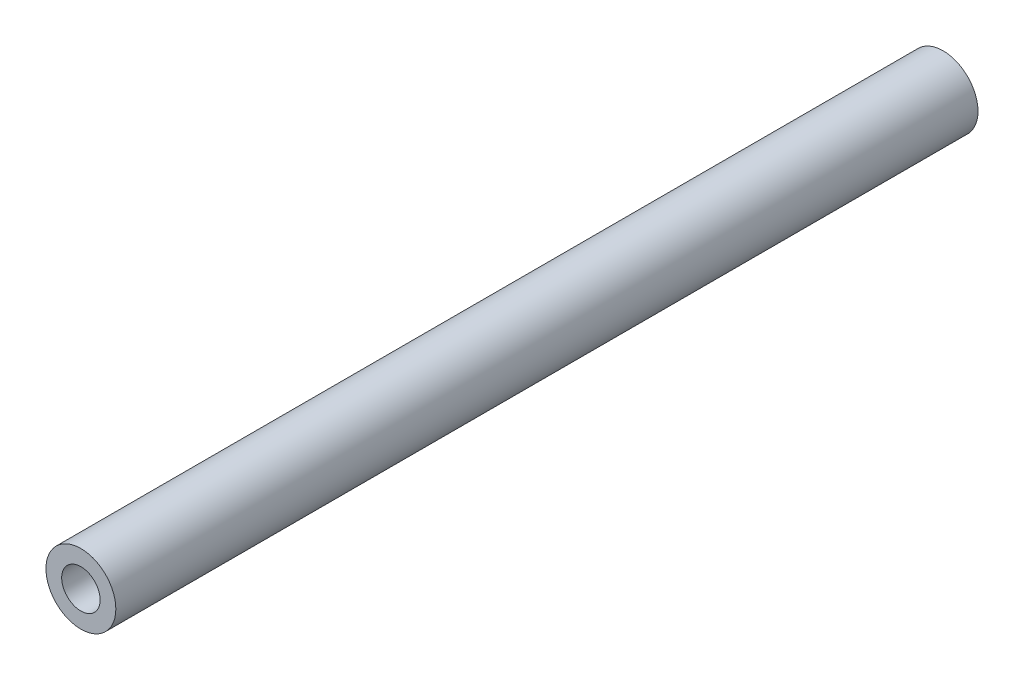
SolidWorks part; units mm, degrees
material "6061 合金"
ref_plane "前视基准面" through (0, 0, 0) normal (0, 0, 1) x (1, 0, 0)
ref_plane "上视基准面" through (0, 0, 0) normal (0, 1, 0) x (1, 0, 0)
ref_plane "右视基准面" through (0, 0, 0) normal (1, 0, 0) x (0, 0, -1)
sketch "草图1" plane through (0, 0, 0) normal (0, 0, 1) x (1, 0, 0)
  circle A1 centre (0, 0) radius 3
  dimension "D1" = 6
extrude "凸台-拉伸1" add sketch "草图1" along normal blind 74
hole_wizard "M4 螺纹孔1" positions "草图2" profile "草图3" tap size "M4" standard "GB" end condition through all
sketch "草图2" plane through (0, 0, 74) normal (0, 0, 1) x (1, 0, 0)
  point P0 (0, 0)
sketch "草图3" plane through (0, 0, 74) normal (1, 0, 0) x (0, -1, 0)
  line L0 (0, 0) -> (0, 74)
  line L1 (0, 74) -> (1.65, 74)
  line L2 (1.65, 74) -> (1.65, 0)
  line L5 (1.65, 0) -> (0, 0)
  line L11 (0, -6.35) -> (0, 107.95) construction
  dimension "通孔螺纹孔钻头直径" = 3.3
  dimension "通孔螺纹孔钻头深度" = 74
cosmetic thread "孔螺蚊线1" parameters "D2"=4
